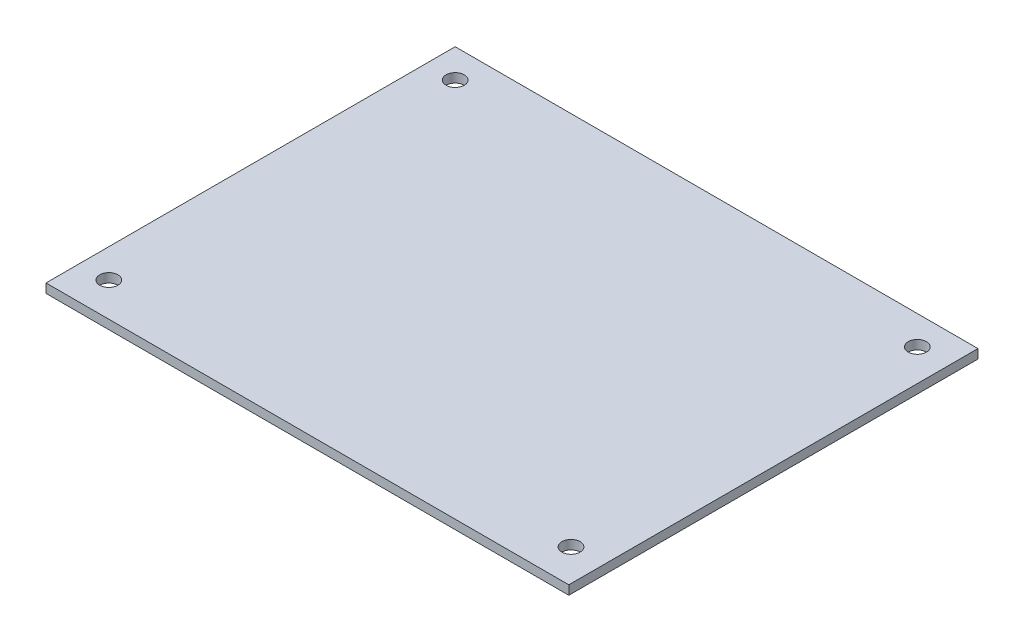
SolidWorks part; units mm, degrees
ref_plane "Front Plane" through (0, 0, 0) normal (0, 0, 1) x (1, 0, 0)
ref_plane "Top Plane" through (0, 0, 0) normal (0, 1, 0) x (1, 0, 0)
ref_plane "Right Plane" through (0, 0, 0) normal (1, 0, 0) x (0, 0, -1)
sketch "Sketch1" plane through (0, 0, 0) normal (0, 1, 0) x (1, 0, 0)
  line L1 (0, 0) -> (92, 0)
  line L2 (0, 0) -> (0, 72)
  line L3 (0, 72) -> (92, 72)
  line L4 (92, 0) -> (92, 72)
  circle A0 centre (5.08, 66.92) radius 1.6
  circle A1 centre (86.412, 66.92) radius 1.6
  circle A2 centre (86.412, 5.969) radius 1.6
  circle A3 centre (5.08, 5.969) radius 1.6
  dimension "D3" = 3.2
  dimension "D1" = 92
  dimension "D2" = 72
  dimension "D4" = 5.08
  dimension "D5" = 5.08
  dimension "D6" = 5.969
  dimension "D7" = 5.588
extrude "Boss-Extrude1" add sketch "Sketch1" along normal blind 1.6 contours L3 L4 L1 L2
sketch "Sketch2" plane through (0, 1.6, 0) normal (0, 1, 0) x (1, 0, 0)
  line L0 (92, 72) -> (0, 72) construction
  line L1 (92, 0) -> (92, 72) construction
  point P0 (76.252, 66.92)
  point P1 (48.566, 66.92)
  point P2 (35.993, 56.506)
  dimension "D1" = 5.08
  dimension "D2" = 15.748
  dimension "D3" = 27.686
  dimension "D4" = 12.573
  dimension "D5" = 10.414
